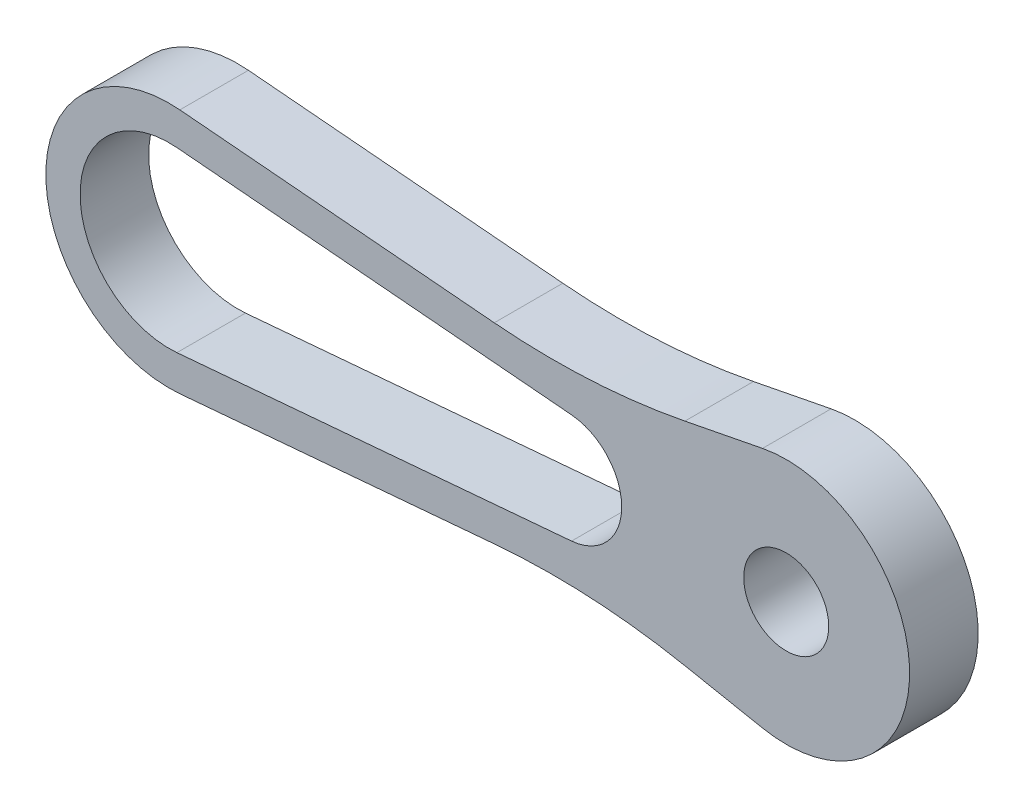
SolidWorks part; units mm, degrees
material "ABS"
ref_plane "Front Plane" through (0, 0, 0) normal (0, 0, 1) x (1, 0, 0)
ref_plane "Top Plane" through (0, 0, 0) normal (0, 1, 0) x (1, 0, 0)
ref_plane "Right Plane" through (0, 0, 0) normal (1, 0, 0) x (0, 0, -1)
sketch "Sketch1" plane through (0, 0, 0) normal (0, 0, 1) x (1, 0, 0)
  line L0 (0.5603, 6.4758) -> (29.3448, 3.9851)
  line L1 (-15.0641, 0) -> (73.4253, 0) construction
  line L2 (0.5603, -6.4758) -> (29.3448, -3.9851)
  arc A0 (0.5603, 6.4758) -> (0.5603, -6.4758) centre (0, 0) ccw
  arc A1 (29.3448, -3.9851) -> (29.3448, 3.9851) centre (29, 0) ccw
  dimension "D1" = 13
  dimension "D3" = 8
  dimension "D2" = 29
sketch "Sketch2" plane through (0, 0, 0) normal (0, 0, 1) x (1, 0, 0)
  line L0 (-15.0641, 0) -> (73.4253, 0) construction
  line L1 (0.7759, 8.9665) -> (23.7054, 6.9824)
  line L2 (0.5603, 6.4758) -> (29.3448, 3.9851) construction
  line L3 (37.6109, 7.7256) -> (43.2729, 8.8327)
  line L4 (90.139, 0) -> (80.0588, 0) construction
  line L5 (0.7759, -8.9665) -> (23.7054, -6.9824)
  line L6 (37.6109, -7.7256) -> (43.2729, -8.8327)
  arc A0 (0.7759, 8.9665) -> (0.7759, -8.9665) centre (0, 0) ccw
  arc A1 (43.2729, -8.8327) -> (43.2729, 8.8327) centre (45, 0) ccw
  arc A3 (23.7054, 6.9824) -> (37.6109, 7.7256) centre (28.0157, 56.7963) ccw
  arc A4 (23.7054, -6.9824) -> (37.6109, -7.7256) centre (28.0157, -56.7963) cw
  dimension "D1" = 18
  dimension "D2" = 18
  dimension "D3" = 50
  dimension "D4" = 45
extrude "Tijelo" add sketch "Sketch2" along normal blind 5
extrude "Utor za ruku" cut sketch "Sketch1" along normal through all
sketch "Sketch3" plane through (0, 0, 0) normal (0, 0, -1) x (-1, 0, 0)
  circle A0 centre (-45, 0) radius 6.65
  dimension "D1" = 13.3
extrude "Spojnica" [suppressed] add sketch "Sketch3" along normal blind 5
sketch "Sketch4" plane through (0, 0, 5) normal (0, 0, 1) x (1, 0, 0)
  line L0 (0, 0) -> (79.0723, 0) construction
  line L2 (40.8431, 0) -> (42.9215, -3.6)
  line L3 (42.9215, -3.6) -> (47.0785, -3.6)
  line L4 (47.0785, -3.6) -> (49.1569, 0)
  line L5 (49.1569, 0) -> (47.0785, 3.6)
  line L6 (47.0785, 3.6) -> (42.9215, 3.6)
  line L7 (42.9215, 3.6) -> (40.8431, 0)
  circle A0 centre (45, 0) radius 4.1569 construction
  dimension "D1" = 7.2
extrude "Utor za maticu" [suppressed] cut sketch "Sketch4" against normal blind 11
sketch "Sketch5" [suppressed] plane through (0, 0, -5) normal (0, 0, -1) x (-1, 0, 0)
  circle A0 centre (-45, 0) radius 2.05
  dimension "D1" = 4.1
extrude "Utor za vijak" [suppressed] cut sketch "Sketch5" against normal blind 38
sketch "Sketch6" [suppressed] plane through (0, 0, 3) normal (0, 0, -1) x (-1, 0, 0)
  circle A0 centre (0, 0) radius 4.975
  dimension "D1" = 9.95
extrude "Provrt za vijak" [suppressed] cut sketch "Sketch6" against normal blind 6
sketch "Sketch8" plane through (0, 0, 0) normal (0, 0, 1) x (1, 0, 0)
  circle A0 centre (45, 0) radius 3.1
  dimension "D1" = 6.2
extrude "Cut-Extrude2" cut sketch "Sketch8" along normal blind 10
